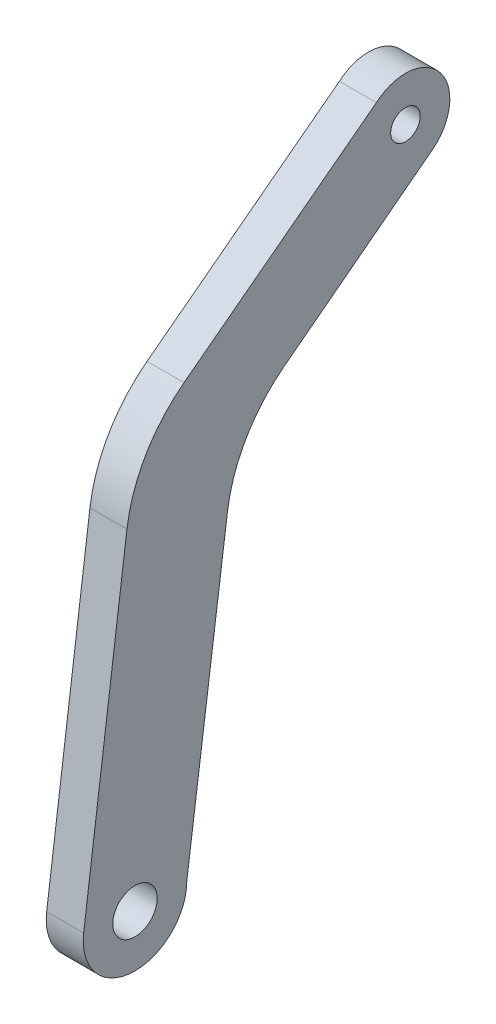
SolidWorks part; units mm, degrees
ref_plane "Спереди" through (0, 0, 0) normal (0, 0, 1) x (1, 0, 0)
ref_plane "Сверху" through (0, 0, 0) normal (0, 1, 0) x (1, 0, 0)
ref_plane "Справа" through (0, 0, 0) normal (1, 0, 0) x (0, 0, -1)
sketch "Эскиз1" plane through (0, 0, 0) normal (1, 0, 0) x (0, 0, -1)
  line L0 (7.5757, -1.4401) -> (-12.4695, -16.7819)
  line L1 (-20.132, -29.9728) -> (-25.6337, -70.4872)
  line L2 (0, 7.8592) -> (-26.0039, -11.922)
  line L3 (-33.7233, -25.2241) -> (-39.5736, -69.5717)
  circle A0 centre (3.929, 3.3245) radius 2
  arc A1 (7.5757, -1.4401) -> (0, 7.8592) centre (3.929, 3.3245) ccw
  circle A2 centre (-32.6337, -70.4872) radius 3
  arc A3 (-39.5736, -69.5717) -> (-25.6337, -70.4872) centre (-32.6337, -70.4872) ccw
  arc A4 (-12.4695, -16.7819) -> (-20.132, -29.9728) centre (-0.3139, -32.664) ccw
  arc A5 (-33.7233, -25.2241) -> (-26.0039, -11.922) centre (-13.8951, -27.8398) cw
  dimension "D1" = 20
extrude "Вытянуть1" add sketch "Эскиз1" along normal blind 5
